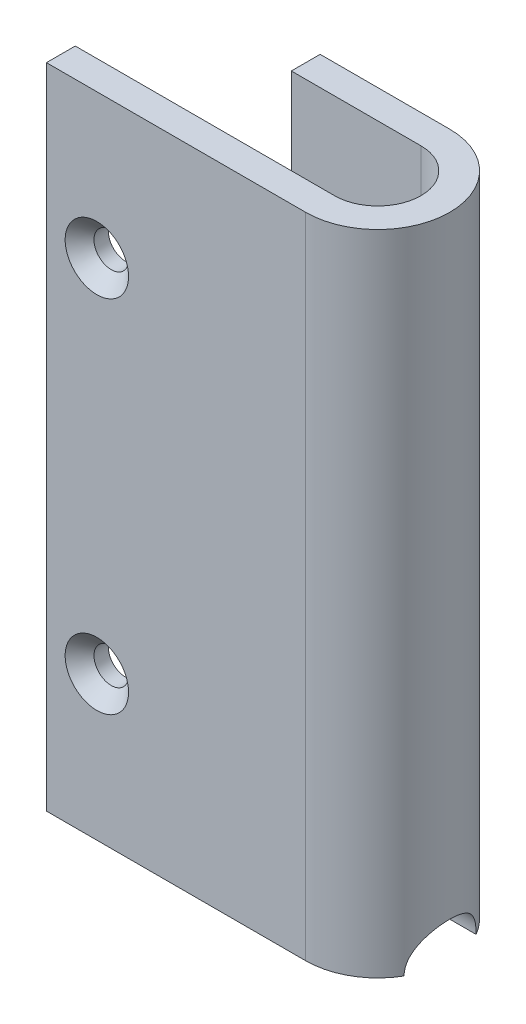
SolidWorks part; units mm, degrees
ref_plane "Front Plane" through (0, 0, 0) normal (0, 0, 1) x (1, 0, 0)
ref_plane "Top Plane" through (0, 0, 0) normal (0, 1, 0) x (1, 0, 0)
ref_plane "Right Plane" through (0, 0, 0) normal (1, 0, 0) x (0, 0, -1)
sketch "Sketch1" plane through (0, 0, 0) normal (0, 1, 0) x (1, 0, 0)
  line L0 (0, 3) -> (-9, 3)
  line L1 (0, -3) -> (-18, -3)
  line L2 (0, -5) -> (-18, -5)
  line L3 (0, 5) -> (-9, 5)
  line L4 (-9, 5) -> (-9, 3)
  line L5 (-18, -3) -> (-18, -5)
  arc A0 (0, -3) -> (0, 3) centre (0, 0) ccw
  arc A1 (0, -5) -> (0, 5) centre (0, 0) ccw
  dimension "D1" = 6
  dimension "D2" = 18
  dimension "D3" = 9
  dimension "D4" = 2
extrude "Boss-Extrude1" add sketch "Sketch1" along normal blind 45
sketch "Sketch2" plane through (0, 0, -5) normal (0, 0, -1) x (-1, 0, 0)
  line L0 (9, 45) -> (9, 0) construction
  line L1 (0, 0) -> (9, 0) construction
  circle A0 centre (9, 17.5) radius 1
  dimension "D1" = 2
  dimension "D2" = 17.5
extrude "Cut-Extrude1" cut sketch "Sketch2" against normal blind 5
sketch "Sketch3" plane through (0, 0, 0) normal (1, 0, 0) x (0, 0, -1)
  circle A0 centre (0, 0) radius 2.5
  dimension "D1" = 5
extrude "Cut-Extrude2" cut sketch "Sketch3" along normal blind 6
sketch "Sketch4" plane through (0, 0, 5) normal (0, 0, 1) x (1, 0, 0)
  line L0 (-18, 45) -> (-14.5, 45) construction
  line L1 (-18, 45) -> (0, 45) construction
  line L2 (-14.5, 45) -> (-14.5, 35) construction
  line L3 (-14.5, 35) -> (-14.5, 10) construction
  dimension "D1" = 3.5
  dimension "D2" = 10
  dimension "D3" = 25
hole_wizard "CSK for M2 Countersunk Flat Head Screw1" positions "3DSketch1" profile "Sketch5" countersink size "M2" standard "DIN" end condition through all
sketch3d "3DSketch1"
  point P0 (-14.5, 35, 5)
  point P3 (-14.5, 10, 5)
sketch "Sketch5" plane through (-14.5, 35, 5) normal (1, 0, 0) x (0, -1, 0)
  line L0 (0, 0) -> (0, 10)
  line L1 (0, 10) -> (1.2, 10)
  line L2 (1.2, 10) -> (1.2, 1)
  line L3 (1.2, 1) -> (2.2, 0)
  line L5 (2.2, 0) -> (0, 0)
  line L6 (-1.2, 1) -> (-2.2, 0) construction
  line L11 (0, -6.35) -> (0, 107.95) construction
  dimension "Thru Hole Dia." = 2.4
  dimension "Thru Hole Depth" = 10
  dimension "Near C'Sink Dia." = 4.4
  dimension "Near C'Sink Angle" = 90
